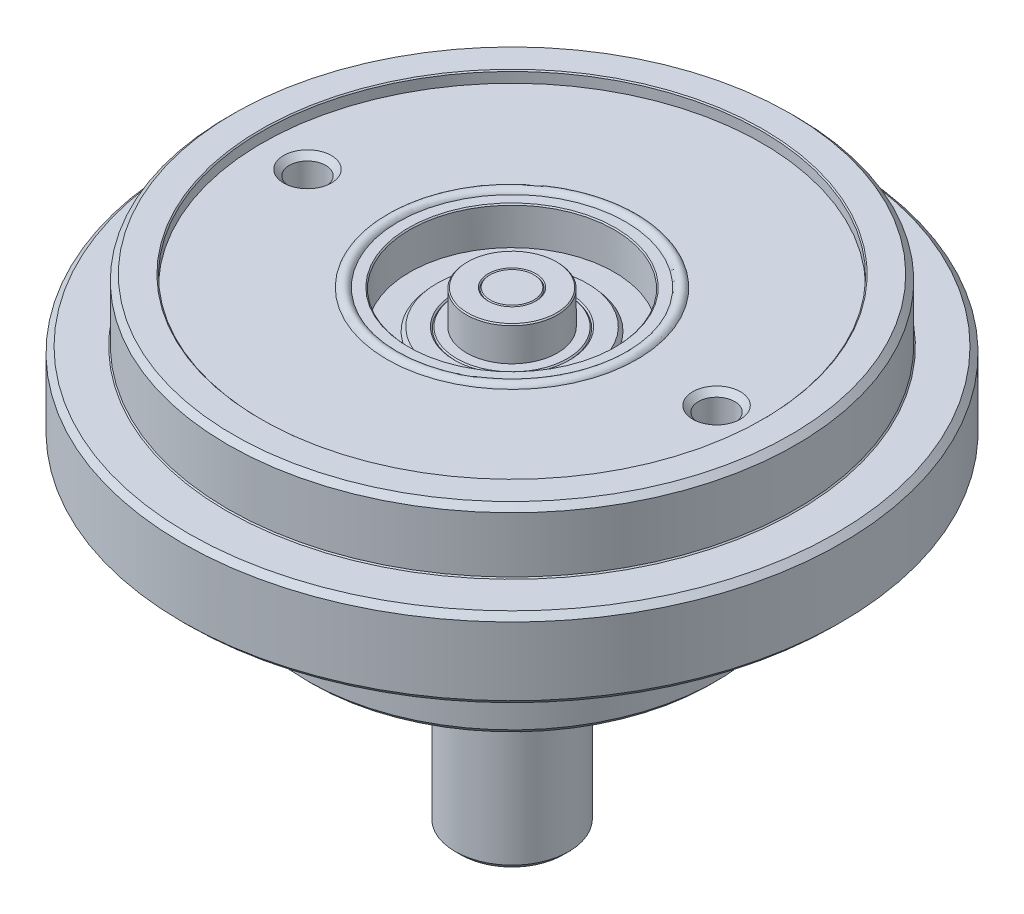
SolidWorks part; units mm, degrees
material "7079 Alloy"
ref_plane "Front Plane" through (0, 0, 0) normal (0, 0, 1) x (1, 0, 0)
ref_plane "Top Plane" through (0, 0, 0) normal (0, 1, 0) x (1, 0, 0)
ref_plane "Right Plane" through (0, 0, 0) normal (1, 0, 0) x (0, 0, -1)
sketch "Sketch1" plane through (0, 0, 0) normal (0, 0, 1) x (1, 0, 0)
  line L0 (844.9432, 281.3889) -> (845.4285, 280.8889)
  line L1 (844.9432, 281.3889) -> (843.3432, 281.3889)
  line L2 (845.4285, 280.8889) -> (849.9424, 280.8889)
  line L3 (831.9424, 300.6704) -> (831.9424, 289.6846) construction
  line L4 (831.9424, 302.3889) -> (831.9424, 261.3889)
  line L5 (856.9424, 303.3889) -> (856.9424, 297.8889)
  line L7 (843.3432, 281.3889) -> (843.016, 281.6197)
  line L8 (836.9424, 261.3889) -> (836.9424, 281.3889)
  line L9 (843.016, 281.6197) -> (838.7918, 281.6197)
  line L10 (836.9424, 281.3889) -> (838.5424, 281.3889)
  line L11 (838.5424, 281.3889) -> (838.7918, 281.6197)
  line L12 (831.9424, 261.3889) -> (836.9424, 261.3889)
  line L13 (831.9424, 302.3889) -> (833.8628, 302.3889)
  line L15 (835.8305, 281.3889) -> (844.9432, 281.3889) construction
  line L16 (835.8305, 281.3889) -> (835.8305, 289.3889) construction
  line L17 (856.9424, 303.3889) -> (853.9424, 303.3889)
  line L18 (835.8305, 289.3889) -> (844.9432, 289.3889) construction
  line L19 (842.9424, 302.3889) -> (853.9424, 302.3889)
  line L21 (844.9432, 281.3889) -> (844.9432, 289.3889) construction
  line L22 (844.9432, 289.3889) -> (839.0782, 289.3889) construction
  line L23 (835.9424, 302.3889) -> (835.9424, 299.3889)
  line L24 (844.9432, 289.3889) -> (844.9432, 291.3889) construction
  line L25 (844.9432, 291.3889) -> (839.0782, 291.3889) construction
  line L26 (839.0782, 289.3889) -> (839.0782, 291.3889) construction
  line L27 (844.9432, 291.3889) -> (835.6621, 291.3889) construction
  line L28 (853.9424, 303.3889) -> (853.9424, 302.3889)
  line L29 (836.8043, 299.3889) -> (835.9424, 299.3889)
  line L33 (840.9424, 299.3889) -> (835.6621, 299.3889) construction
  line L34 (849.9424, 280.8889) -> (849.9424, 290.8889)
  line L35 (860.9424, 290.8889) -> (849.9424, 290.8889)
  line L36 (860.9424, 290.8889) -> (860.9424, 297.8889)
  line L37 (835.6621, 291.3889) -> (835.6621, 299.3889) construction
  line L38 (856.9424, 297.8889) -> (860.9424, 297.8889)
  line L40 (840.9424, 299.055) -> (838.8501, 299.055)
  line L41 (834.0382, 302.3889) -> (835.9424, 302.3889)
  line L42 (833.9424, 302.3016) -> (834.0382, 302.3889)
  line L43 (833.9424, 302.3016) -> (833.8628, 302.3889)
  line L44 (841.9424, 302.3889) -> (840.9424, 302.3889)
  line L45 (838.8501, 299.055) -> (838.5565, 299.3889)
  line L46 (838.5565, 299.3889) -> (837.0225, 299.3889)
  line L47 (840.9424, 302.3889) -> (840.9424, 299.055)
  line L49 (836.8043, 299.3889) -> (836.9047, 299.2801)
  line L50 (836.9047, 299.2801) -> (837.0225, 299.3889)
  arc A0 (842.9424, 302.3889) -> (841.9424, 302.3889) centre (842.4424, 302.1662) ccw
  dimension "D1" = 10
  dimension "D4" = 19.5
  dimension "D6" = 4
  dimension "D7" = 1.6
  dimension "D8" = 1.6
  dimension "D9" = 1
  dimension "D17" = 25
  dimension "D18" = 22
  dimension "D24" = 8
  dimension "D25" = 2
  dimension "D28" = 7
  dimension "D30" = 3
revolve "Revolve4" add sketch "Sketch1" angle 360 about L3
sketch "Sketch2" plane through (0, 302.3889, 0) normal (0, 1, 0) x (-1, 0, 0)
  line L0 (-812.4362, 0) -> (-853.4389, 0) construction
  circle A0 centre (-849.9424, 0) radius 1.6
  circle A1 centre (-813.9424, 0) radius 1.6
  dimension "D3" = 3.2
  dimension "D4" = 3.2
extrude "Cut-Extrude2" cut sketch "Sketch2" against normal blind 6
sketch "Sketch3" plane through (0, 296.3889, 0) normal (0, 1, 0) x (-1, 0, 0)
  circle A2 centre (-849.9424, 0) radius 1.6
  circle A3 centre (-849.9424, 0) radius 1.6
  circle A5 centre (-813.9424, 0) radius 1.6
  circle A6 centre (-813.9424, 0) radius 1.6
  dimension "D1" = 0
  dimension "D2" = 0
extrude "Cut-Extrude3" cut sketch "Sketch3" against normal blind 2 draft 55
sketch "Sketch4" plane through (0, 290.8889, 0) normal (0, -1, 0) x (1, 0, 0)
  line L0 (831.9424, 0) -> (831.9424, -31.4487) construction
  circle A0 centre (831.9424, 0) radius 24 construction
  circle A1 centre (831.9424, -24) radius 1.2
  circle A2 centre (811.1578, 12) radius 1.2
  circle A3 centre (852.727, 12) radius 1.2
  dimension "D1" = 48
  dimension "D2" = 2.4
extrude "Cut-Extrude4" cut sketch "Sketch4" against normal blind 5
sketch "Sketch5" plane through (0, 295.8889, 0) normal (0, -1, 0) x (1, 0, 0)
  circle A2 centre (831.9424, -24) radius 1.2
  circle A3 centre (831.9424, -24) radius 1.2
  circle A5 centre (852.727, 12) radius 1.2
  circle A6 centre (852.727, 12) radius 1.2
  circle A8 centre (811.1578, 12) radius 1.2
  circle A9 centre (811.1578, 12) radius 1.2
  dimension "D1" = 0
  dimension "D2" = 0
  dimension "D3" = 0
extrude "Cut-Extrude5" cut sketch "Sketch5" against normal blind 2 draft 55
chamfer "Chamfer1" distance 0.5 angle 45 10 edges at (831.9424, 290.8889, 29) (831.9424, 297.8889, 29) (831.9424, 280.8889, 18) (831.9424, 303.3889, 25) (831.9424, 290.8889, -25.2) (852.727, 290.8889, 10.8) (811.1578, 290.8889, 10.8) (849.9424, 302.3889, 1.6) (813.9424, 302.3889, 1.6) (831.9424, 261.3889, 5)
chamfer "Chamfer3" distance 0.1 angle 45 5 edges at (831.9424, 303.3889, 22) (831.9424, 302.3889, 4) (831.9424, 302.3889, 9) (831.9424, 290.8889, 18) (831.9424, 297.8889, 25)
